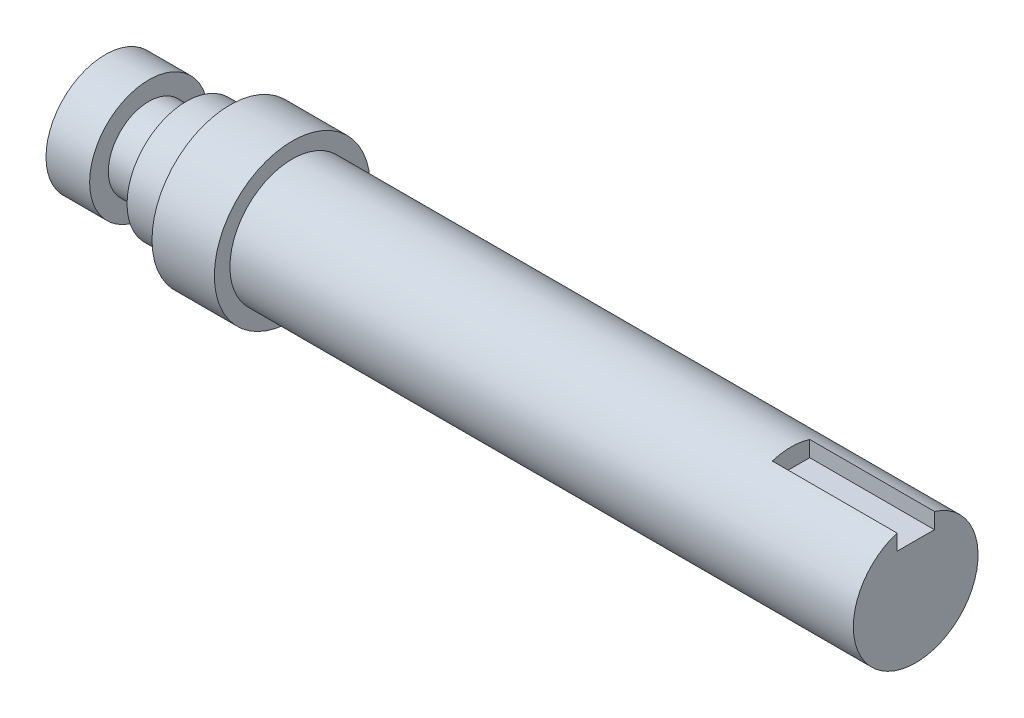
SolidWorks part; units mm, degrees
material "AISI 1045 Çelik, soğuk çekilmiş"
ref_plane "Ön Düzlem" through (0, 0, 0) normal (0, 0, 1) x (1, 0, 0)
ref_plane "Üst Düzlem" through (0, 0, 0) normal (0, 1, 0) x (1, 0, 0)
ref_plane "Sağ Düzlem" through (0, 0, 0) normal (1, 0, 0) x (0, 0, -1)
sketch "Çizim2" plane through (0, 0, 0) normal (0, 0, 1) x (1, 0, 0)
  line L0 (0, 0) -> (0, 10)
  line L1 (0, 10) -> (-100, 10)
  line L2 (-100, 10) -> (-100, 12.5)
  line L3 (-100, 12.5) -> (-110, 12.5)
  line L4 (-110, 12.5) -> (-110, 9.5)
  line L5 (-110, 9.5) -> (-130, 9.5)
  line L6 (-130, 9.5) -> (-130, 0)
  line L7 (-130, 0) -> (0, 0)
  dimension "D1" = 10
  dimension "D2" = 100
  dimension "D3" = 20
  dimension "D4" = 10
  dimension "D5" = 9.5
  dimension "D6" = 12.5
revolve "Döndür1" add sketch "Çizim2" angle 360 about L7
sketch "Çizim3" plane through (0, 0, 0) normal (0, 0, 1) x (1, 0, 0)
  line L0 (-110, 9.5) -> (-130, 9.5) construction
  line L1 (-123, 9.5) -> (-117, 9.5)
  line L2 (-123, 9.5) -> (-123, 6.5)
  line L3 (-123, 6.5) -> (-117, 6.5)
  line L4 (-117, 9.5) -> (-117, 6.5)
  line L5 (-130, 9.5) -> (-130, -9.5) construction
  line L6 (-130, 0) -> (-94.0212, 0) construction
  dimension "D1" = 3
  dimension "D2" = 6
  dimension "D3" = 7
revolve "Kes-Döndür1" cut sketch "Çizim3" angle 360 about L6
sketch "Çizim4" plane through (0, 0, 0) normal (0, 0, 1) x (1, 0, 0)
  line L0 (0, -10) -> (0, 10) construction
  line L1 (0, 12) -> (-20, 12)
  line L2 (0, 12) -> (0, 7)
  line L3 (0, 7) -> (-20, 7)
  line L4 (-20, 12) -> (-20, 7)
  dimension "D1" = 3
  dimension "D2" = 20
  dimension "D3" = 20
  dimension "D4" = 5
extrude "Kes-Ekstrüzyon1" cut sketch "Çizim4" against normal mid plane 6
